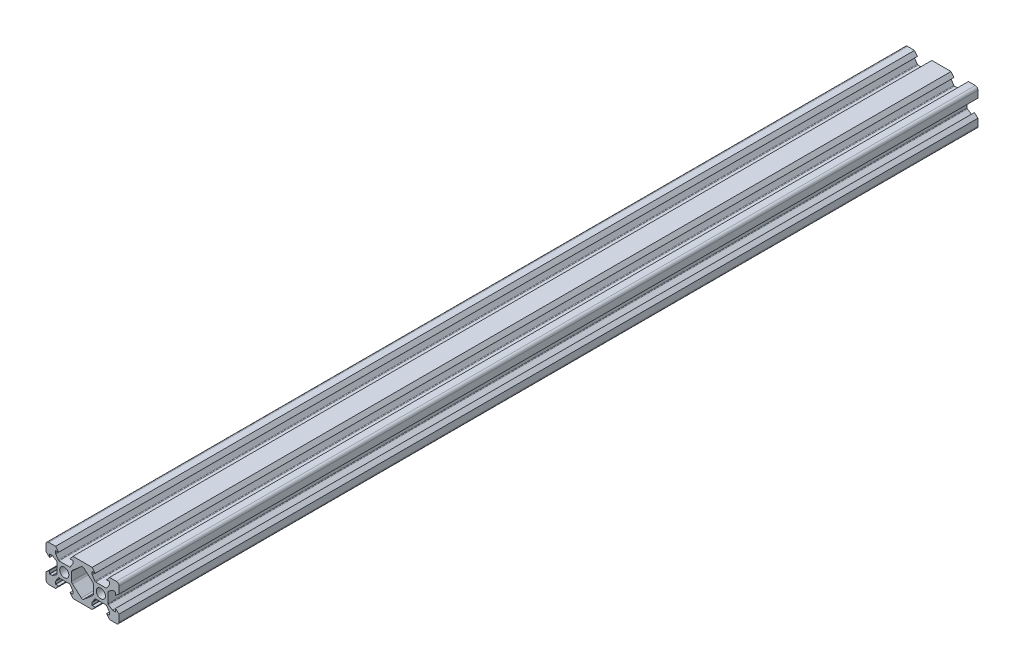
SolidWorks part; units mm, degrees
ref_plane "Спереди" through (0, 0, 0) normal (0, 0, 1) x (1, 0, 0)
ref_plane "Сверху" through (0, 0, 0) normal (0, 1, 0) x (1, 0, 0)
ref_plane "Справа" through (0, 0, 0) normal (1, 0, 0) x (0, 0, -1)
sketch "Эскиз1" plane through (0, 0, 0) normal (0, 0, 1) x (1, 0, 0)
  line L0 (-10, 17.7205) -> (-10, -8.2094) construction
  line L1 (-18.5, 14.0769) -> (-14.75, 14.0769)
  line L2 (-20, 12.5769) -> (-20, 8.8269)
  line L3 (-18.5, -5.9231) -> (-14.75, -5.9231)
  line L4 (20, 12.5769) -> (20, 8.8269)
  line L5 (10, 18.3173) -> (10, -8.2094) construction
  line L6 (0, 14.0769) -> (0, -5.9231) construction
  line L7 (-20, 4.0769) -> (20, 4.0769) construction
  line L8 (-10, 4.0769) -> (-10, 6.5769)
  line L9 (-20, -0.6731) -> (-20, -4.4231)
  line L10 (-18, 7.1769) -> (-18, 8.7269)
  line L11 (-14, 6.9078) -> (-14, 1.246)
  line L12 (-20, 8.8269) -> (-18, 7.1769)
  line L13 (-20, -0.6731) -> (-18, 0.9769)
  line L14 (-18, 0.9769) -> (-18, -0.5731)
  line L15 (-17.9, 8.8269) -> (-16.6501, 8.8269)
  line L16 (-16.3747, 8.7442) -> (-14.2246, 7.3251)
  line L17 (-16.3747, -0.5904) -> (-14.2246, 0.8287)
  line L18 (-17.9, -0.6731) -> (-16.6501, -0.6731)
  line L19 (20, 8.8269) -> (18, 7.1769)
  line L20 (20, -0.6731) -> (18, 0.9769)
  line L21 (17.9, -0.6731) -> (16.6501, -0.6731)
  line L22 (16.3747, -0.5904) -> (14.2246, 0.8287)
  line L23 (17.9, 8.8269) -> (16.6501, 8.8269)
  line L24 (18, 0.9769) -> (18, -0.5731)
  line L25 (14, 6.9078) -> (14, 1.246)
  line L26 (18, 7.1769) -> (18, 8.7269)
  line L27 (16.3747, 8.7442) -> (14.2246, 7.3251)
  line L28 (20, -0.6731) -> (20, -4.4231)
  line L29 (-14.75, 14.0769) -> (-13.1, 12.0769)
  line L30 (-13.1, 12.0769) -> (-14.65, 12.0769)
  line L31 (-14.75, 11.9769) -> (-14.75, 10.727)
  line L32 (-14.6673, 10.4516) -> (-13.2482, 8.3015)
  line L33 (-7.1691, 8.0769) -> (-12.8309, 8.0769)
  line L34 (-5.3327, 10.4516) -> (-6.7518, 8.3015)
  line L35 (-5.25, 11.9769) -> (-5.25, 10.727)
  line L36 (-6.9, 12.0769) -> (-5.35, 12.0769)
  line L37 (-5.25, 14.0769) -> (-6.9, 12.0769)
  line L38 (0, 8.8269) -> (-2, 7.1769) [skipped]
  line L39 (-2, 7.1769) -> (-2, 8.7269) [skipped]
  line L40 (-2.1, 8.8269) -> (-3.3499, 8.8269) [skipped]
  line L41 (-3.6253, 8.7442) -> (-5.7754, 7.3251) [skipped]
  line L42 (-6, 1.246) -> (-6, 6.9078) [skipped]
  line L43 (-3.6253, -0.5904) -> (-5.7754, 0.8287) [skipped]
  line L44 (-2.1, -0.6731) -> (-3.3499, -0.6731) [skipped]
  line L45 (-2, 0.9769) -> (-2, -0.5731) [skipped]
  line L46 (0, -0.6731) -> (-2, 0.9769) [skipped]
  line L47 (-5.25, -5.9231) -> (-6.9, -3.9231)
  line L48 (-6.9, -3.9231) -> (-5.35, -3.9231)
  line L49 (-5.25, -3.8231) -> (-5.25, -2.5733)
  line L50 (-5.3327, -2.2978) -> (-6.7518, -0.1477)
  line L51 (-12.8309, 0.0769) -> (-7.1691, 0.0769)
  line L52 (-14.6673, -2.2978) -> (-13.2482, -0.1477)
  line L53 (-14.75, -3.8231) -> (-14.75, -2.5733)
  line L54 (-13.1, -3.9231) -> (-14.65, -3.9231)
  line L55 (-14.75, -5.9231) -> (-13.1, -3.9231)
  line L56 (14.75, -5.9231) -> (13.1, -3.9231)
  line L57 (13.1, -3.9231) -> (14.65, -3.9231)
  line L58 (14.75, -3.8231) -> (14.75, -2.5733)
  line L59 (14.6673, -2.2978) -> (13.2482, -0.1477)
  line L60 (12.8309, 0.0769) -> (7.1691, 0.0769)
  line L61 (5.3327, -2.2978) -> (6.7518, -0.1477)
  line L62 (5.25, -3.8231) -> (5.25, -2.5733)
  line L63 (6.9, -3.9231) -> (5.35, -3.9231)
  line L64 (5.25, -5.9231) -> (6.9, -3.9231)
  line L65 (0, -0.6731) -> (2, 0.9769) [skipped]
  line L66 (2, 0.9769) -> (2, -0.5731) [skipped]
  line L67 (2.1, -0.6731) -> (3.3499, -0.6731) [skipped]
  line L68 (3.6253, -0.5904) -> (5.7754, 0.8287) [skipped]
  line L69 (6, 1.246) -> (6, 6.9078) [skipped]
  line L70 (3.6253, 8.7442) -> (5.7754, 7.3251) [skipped]
  line L71 (2.1, 8.8269) -> (3.3499, 8.8269) [skipped]
  line L72 (2, 7.1769) -> (2, 8.7269) [skipped]
  line L73 (0, 8.8269) -> (2, 7.1769) [skipped]
  line L74 (5.25, 14.0769) -> (6.9, 12.0769)
  line L75 (6.9, 12.0769) -> (5.35, 12.0769)
  line L76 (5.25, 11.9769) -> (5.25, 10.727)
  line L77 (5.3327, 10.4516) -> (6.7518, 8.3015)
  line L78 (7.1691, 8.0769) -> (12.8309, 8.0769)
  line L79 (14.6673, 10.4516) -> (13.2482, 8.3015)
  line L80 (14.75, 11.9769) -> (14.75, 10.727)
  line L81 (13.1, 12.0769) -> (14.65, 12.0769)
  line L82 (14.75, 14.0769) -> (13.1, 12.0769)
  line L83 (-5.25, 14.0769) -> (5.25, 14.0769)
  line L84 (-5.25, -5.9231) -> (5.25, -5.9231)
  line L85 (14.75, -5.9231) -> (18.5, -5.9231)
  line L86 (14.75, 14.0769) -> (18.5, 14.0769)
  line L87 (-6, 6.2202) -> (-6, 1.9336)
  line L88 (5.479, 0.7971) -> (0.6527, -3.3608)
  line L89 (-5.479, 7.3566) -> (-0.6527, 11.5146)
  line L90 (6, 6.2202) -> (6, 1.9336)
  line L91 (5.35, -3.9231) -> (5.3283, -4.1264)
  line L92 (-5.479, 0.7971) -> (-0.6527, -3.3608)
  line L93 (5.479, 7.3566) -> (0.6527, 11.5146)
  arc A0 (20, 12.5769) -> (18.5, 14.0769) centre (18.5, 12.5769) ccw
  arc A1 (-18.5, 14.0769) -> (-20, 12.5769) centre (-18.5, 12.5769) ccw
  arc A2 (18.5, -5.9231) -> (20, -4.4231) centre (18.5, -4.4231) ccw
  arc A3 (-18.5, -5.9231) -> (-20, -4.4231) centre (-18.5, -4.4231) cw
  circle A4 centre (-10, 4.0769) radius 2.5
  circle A5 centre (10, 4.0769) radius 2.5
  arc A6 (-14, 1.246) -> (-14.2246, 0.8287) centre (-14.5, 1.246) cw
  arc A7 (-14.2246, 7.3251) -> (-14, 6.9078) centre (-14.5, 6.9078) cw
  arc A8 (-16.3747, 8.7442) -> (-16.6501, 8.8269) centre (-16.6501, 8.3269) ccw
  arc A9 (-16.3747, -0.5904) -> (-16.6501, -0.6731) centre (-16.6501, -0.1731) cw
  arc A10 (-17.9, 8.8269) -> (-18, 8.7269) centre (-17.9, 8.7269) ccw
  arc A11 (-18, -0.5731) -> (-17.9, -0.6731) centre (-17.9, -0.5731) ccw
  arc A12 (18, -0.5731) -> (17.9, -0.6731) centre (17.9, -0.5731) cw
  arc A13 (17.9, 8.8269) -> (18, 8.7269) centre (17.9, 8.7269) cw
  arc A14 (16.3747, -0.5904) -> (16.6501, -0.6731) centre (16.6501, -0.1731) ccw
  arc A15 (16.3747, 8.7442) -> (16.6501, 8.8269) centre (16.6501, 8.3269) cw
  arc A16 (14.2246, 7.3251) -> (14, 6.9078) centre (14.5, 6.9078) ccw
  arc A17 (14, 1.246) -> (14.2246, 0.8287) centre (14.5, 1.246) ccw
  arc A18 (-14.65, 12.0769) -> (-14.75, 11.9769) centre (-14.65, 11.9769) ccw
  arc A19 (-14.6673, 10.4516) -> (-14.75, 10.727) centre (-14.25, 10.727) cw
  arc A20 (-12.8309, 8.0769) -> (-13.2482, 8.3015) centre (-12.8309, 8.5769) cw
  arc A21 (-6.7518, 8.3015) -> (-7.1691, 8.0769) centre (-7.1691, 8.5769) cw
  arc A22 (-5.3327, 10.4516) -> (-5.25, 10.727) centre (-5.75, 10.727) ccw
  arc A23 (-5.25, 11.9769) -> (-5.35, 12.0769) centre (-5.35, 11.9769) ccw
  arc A24 (-2, 8.7269) -> (-2.1, 8.8269) centre (-2.1, 8.7269) ccw [skipped]
  arc A25 (-3.6253, 8.7442) -> (-3.3499, 8.8269) centre (-3.3499, 8.3269) cw [skipped]
  arc A26 (-6, 6.9078) -> (-5.7754, 7.3251) centre (-5.5, 6.9078) cw [skipped]
  arc A27 (-5.7754, 0.8287) -> (-6, 1.246) centre (-5.5, 1.246) cw [skipped]
  arc A28 (-3.6253, -0.5904) -> (-3.3499, -0.6731) centre (-3.3499, -0.1731) ccw [skipped]
  arc A29 (-2.1, -0.6731) -> (-2, -0.5731) centre (-2.1, -0.5731) ccw [skipped]
  arc A30 (-5.35, -3.9231) -> (-5.25, -3.8231) centre (-5.35, -3.8231) ccw
  arc A31 (-5.3327, -2.2978) -> (-5.25, -2.5733) centre (-5.75, -2.5733) cw
  arc A32 (-7.1691, 0.0769) -> (-6.7518, -0.1477) centre (-7.1691, -0.4231) cw
  arc A33 (-13.2482, -0.1477) -> (-12.8309, 0.0769) centre (-12.8309, -0.4231) cw
  arc A34 (-14.6673, -2.2978) -> (-14.75, -2.5733) centre (-14.25, -2.5733) ccw
  arc A35 (-14.75, -3.8231) -> (-14.65, -3.9231) centre (-14.65, -3.8231) ccw
  arc A36 (14.75, -3.8231) -> (14.65, -3.9231) centre (14.65, -3.8231) cw
  arc A37 (14.6673, -2.2978) -> (14.75, -2.5733) centre (14.25, -2.5733) cw
  arc A38 (13.2482, -0.1477) -> (12.8309, 0.0769) centre (12.8309, -0.4231) ccw
  arc A39 (7.1691, 0.0769) -> (6.7518, -0.1477) centre (7.1691, -0.4231) ccw
  arc A40 (5.3327, -2.2978) -> (5.25, -2.5733) centre (5.75, -2.5733) ccw
  arc A41 (5.35, -3.9231) -> (5.25, -3.8231) centre (5.35, -3.8231) cw
  arc A42 (2.1, -0.6731) -> (2, -0.5731) centre (2.1, -0.5731) cw [skipped]
  arc A43 (3.6253, -0.5904) -> (3.3499, -0.6731) centre (3.3499, -0.1731) cw [skipped]
  arc A44 (5.7754, 0.8287) -> (6, 1.246) centre (5.5, 1.246) ccw [skipped]
  arc A45 (6, 6.9078) -> (5.7754, 7.3251) centre (5.5, 6.9078) ccw [skipped]
  arc A46 (3.6253, 8.7442) -> (3.3499, 8.8269) centre (3.3499, 8.3269) ccw [skipped]
  arc A47 (2, 8.7269) -> (2.1, 8.8269) centre (2.1, 8.7269) cw [skipped]
  arc A48 (5.25, 11.9769) -> (5.35, 12.0769) centre (5.35, 11.9769) cw
  arc A49 (5.3327, 10.4516) -> (5.25, 10.727) centre (5.75, 10.727) cw
  arc A50 (6.7518, 8.3015) -> (7.1691, 8.0769) centre (7.1691, 8.5769) ccw
  arc A51 (12.8309, 8.0769) -> (13.2482, 8.3015) centre (12.8309, 8.5769) ccw
  arc A52 (14.6673, 10.4516) -> (14.75, 10.727) centre (14.25, 10.727) ccw
  arc A53 (14.65, 12.0769) -> (14.75, 11.9769) centre (14.65, 11.9769) cw
  arc A54 (-6, 1.9336) -> (-5.479, 0.7971) centre (-4.5, 1.9336) ccw
  arc A55 (-6, 6.2202) -> (-5.479, 7.3566) centre (-4.5, 6.2202) cw
  arc A56 (6, 1.9336) -> (5.479, 0.7971) centre (4.5, 1.9336) cw
  arc A57 (6, 6.2202) -> (5.479, 7.3566) centre (4.5, 6.2202) ccw
  arc A58 (0.6527, -3.3608) -> (-0.6527, -3.3608) centre (0, -2.6032) cw
  arc A59 (0.6527, 11.5146) -> (-0.6527, 11.5146) centre (0, 10.7569) ccw
  point P0 (0, 0)
  point P8 (20, 14.0769)
  point P11 (-20, 14.0769)
  point P14 (20, -5.9231)
  point P42 (-14, 0.9769)
  point P45 (-14, 7.1769)
  point P48 (-16.5, 8.8269)
  point P51 (-16.5, -0.6731)
  point P54 (-18, 8.8269)
  point P57 (-18, -0.6731)
  point P80 (18, -0.6731)
  point P81 (18, 8.8269)
  point P82 (16.5, -0.6731)
  point P83 (16.5, 8.8269)
  point P84 (14, 7.1769)
  point P85 (14, 0.9769)
  point P155 (-10, 4.0769)
  point P178 (13.1, 0.0769)
  point P201 (6, 0.9769)
  point P224 (6.9, 8.0769)
  point P225 (10, 4.0769)
  point P230 (-6, 1.246)
  point P233 (-6, 6.9078)
  point P242 (0, -3.9231)
  point P245 (0, 12.0769)
  dimension "D3" = 1.5
  dimension "D4" = 1.5
  dimension "D6" = 5
  dimension "D8" = 0.5
  dimension "D9" = 0.5
  dimension "D10" = 0.1
  dimension "D13" = 1.5
  dimension "D14" = 1
  dimension "D1" = 40
  dimension "D2" = 20
  dimension "D5" = 2
  dimension "D7" = 6
  dimension "D11" = 4
  dimension "D12" = 4
sketch "Эскиз2" plane through (0, 0, 0) normal (0, 0, 1) x (1, 0, 0)
sketch "Эскиз3" plane through (0, 0, 0) normal (0, 0, 1) x (1, 0, 0)
extrude "Бобышка-Вытянуть1" add sketch "Эскиз1" against normal blind 470 contours L81 A53 L80 A52 L79 A51 L78 A50 L77 A49 L76 A48 L75 L74 L83 L37 L36 A23 L35 A22 L34 A21 L33 A20 L32 A19 L31 A18 L30 L29 L1 A1 L2 L12 L10 A10 L15 A8 L16 A7 L11 A6 L17 A9 L18 A11 L14 L13 L9 A3 L3
